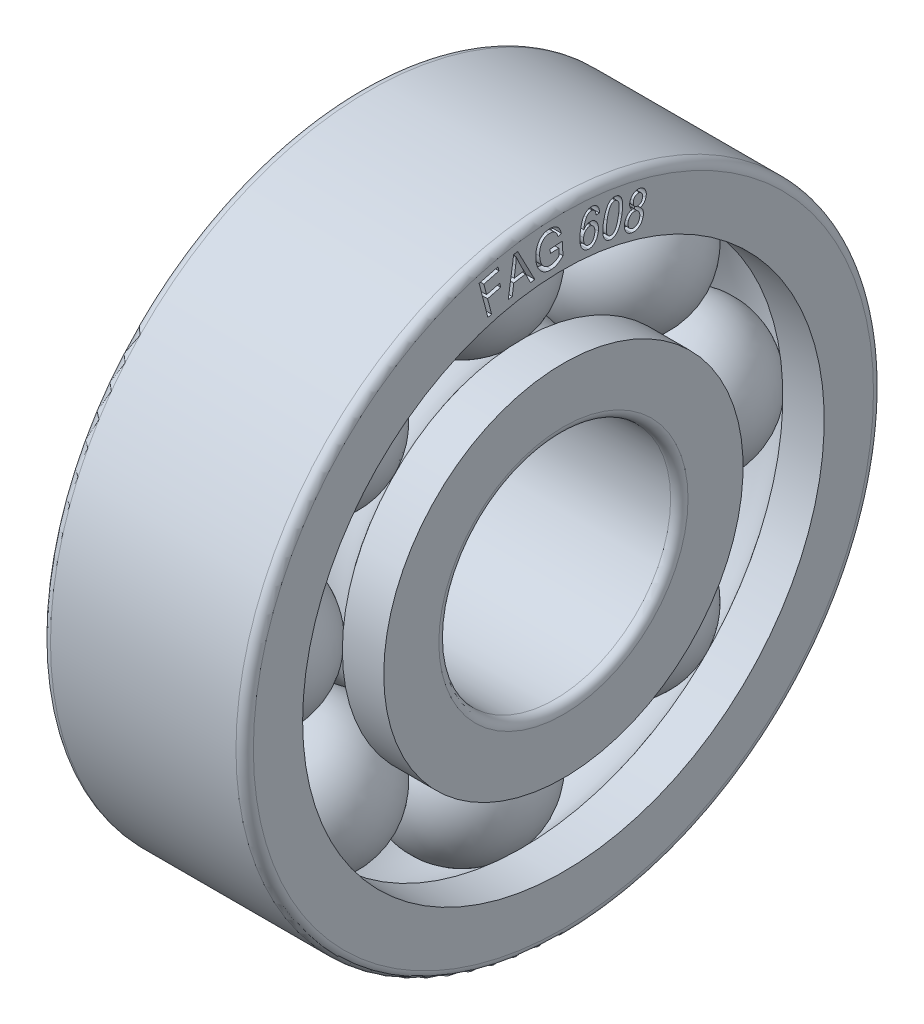
SolidWorks part; units mm, degrees
material "Cast Alloy Steel"
ref_plane "Alzado" through (0, 0, 0) normal (0, 0, 1) x (1, 0, 0)
ref_plane "Planta" through (0, 0, 0) normal (0, 1, 0) x (1, 0, 0)
ref_plane "Vista lateral" through (0, 0, 0) normal (1, 0, 0) x (0, 0, -1)
sketch "Sketch1" plane through (0, 0, 0) normal (0, 0, 1) x (1, 0, 0)
  line L0 (0, 0) -> (29.9021, 0) construction
  line L1 (0, 9) -> (1.4288, 9)
  line L2 (0, 11) -> (7, 11)
  line L3 (0, 11) -> (0, 9)
  line L4 (0, 4) -> (7, 4)
  line L5 (7, 11) -> (7, 9)
  line L6 (0, 6.2) -> (1.4288, 6.2)
  line L7 (0, 6.2) -> (0, 4)
  line L8 (7, 6.2) -> (7, 4)
  line L9 (0, 9) -> (0, 6.2) construction
  line L10 (0, 7.6) -> (7, 7.6) construction
  line L11 (5.5712, 6.2) -> (7, 6.2)
  line L12 (5.5712, 9) -> (7, 9)
  arc A0 (1.4288, 6.2) -> (5.5712, 6.2) centre (3.5, 7.6) ccw
  arc A1 (5.5712, 9) -> (1.4288, 9) centre (3.5, 7.6) ccw
  dimension "D6" = 5
  dimension "D1" = 7
  dimension "D2" = 4
  dimension "D3" = 11
  dimension "D4" = 9
  dimension "D5" = 6.2
revolve "Revolve1" add sketch "Sketch1" angle 360 about L0
fillet "Fillet1" radius 0.3 2 edges at (0, 0, 11) (7, 0, 11)
fillet "Fillet2" radius 0.3 2 edges at (0, 0, 4) (7, 0, 4)
sketch "Sketch2" plane through (0, 0, 0) normal (0, 0, 1) x (1, 0, 0)
  line L0 (3.5, 10.1) -> (3.5, 5.1)
  arc A0 (3.5, 10.1) -> (3.5, 5.1) centre (3.5, 7.6) ccw
  arc A1 (5.5712, 9) -> (1.4288, 9) centre (3.5, 7.6) ccw construction
revolve "Revolve2" add sketch "Sketch2" angle 360 about L0
pattern_circular "CirPattern2" count 8 over 360 about axis through (0, 0, 0) along (1, 0, 0) of bodies 103
sketch "Sketch4" plane through (7, 0, 0) normal (1, 0, 0) x (0, 0, -1)
  arc A0 (-3.1506, 8.6969) -> (3.1506, 8.6969) centre (0, 0) cw construction
  circle A1 centre (0, 0) radius 9 construction
  text T0 "FAG 608" font "Arial Narrow" height 1.2
  dimension "D1" = 9.25
extrude "Cut-Extrude1" cut sketch "Sketch4" against normal blind 0.3
